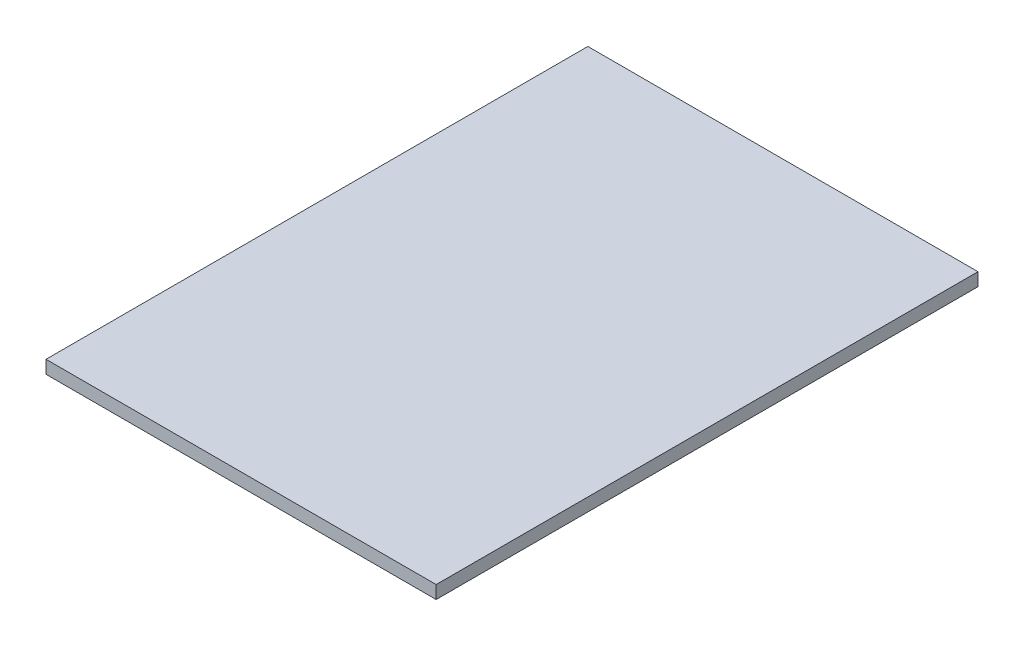
SolidWorks part; units mm, degrees
ref_plane "Front Plane" through (0, 0, 0) normal (0, 0, 1) x (1, 0, 0)
ref_plane "Top Plane" through (0, 0, 0) normal (0, 1, 0) x (1, 0, 0)
ref_plane "Right Plane" through (0, 0, 0) normal (1, 0, 0) x (0, 0, -1)
sketch "Sketch1" plane through (0, 0, 0) normal (0, 1, 0) x (1, 0, 0)
  line L1 (-90, 125) -> (90, 125)
  line L2 (-90, 125) -> (-90, -125)
  line L3 (-90, -125) -> (90, -125)
  line L4 (90, 125) -> (90, -125)
  point P4 (0, 125)
  point P6 (-90, 0)
  dimension "D1" = 180
  dimension "D2" = 250
extrude "Boss-Extrude1" add sketch "Sketch1" along normal blind 6
